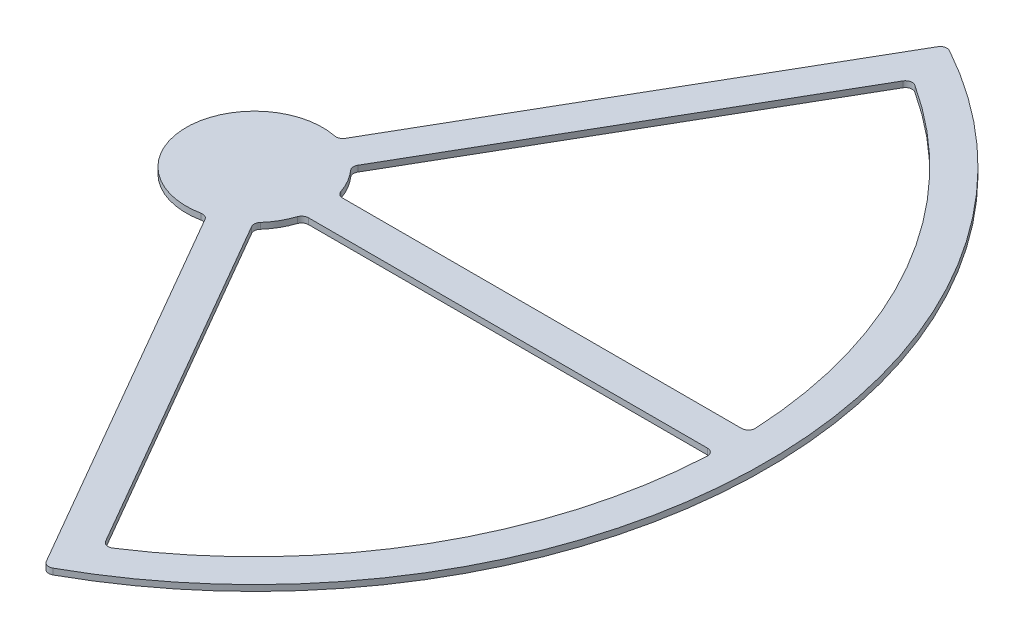
SolidWorks part; units mm, degrees
ref_plane "Front Plane" through (0, 0, 0) normal (0, 0, 1) x (1, 0, 0)
ref_plane "Top Plane" through (0, 0, 0) normal (0, 1, 0) x (1, 0, 0)
ref_plane "Right Plane" through (0, 0, 0) normal (1, 0, 0) x (0, 0, -1)
sketch "Sketch1" plane through (0, 0, 0) normal (0, 1, 0) x (1, 0, 0)
  line L0 (0, 0) -> (150, 0) construction
  line L1 (0, 0) -> (75, 129.9038) construction
  line L2 (0, 0) -> (75, -129.9038) construction
  line L3 (20.8567, 5) -> (137.8223, 5)
  line L4 (20.8567, -5) -> (137.8223, -5)
  line L5 (14.7585, 15.5624) -> (73.2413, 116.8577)
  line L6 (6.0982, 20.5624) -> (69.6547, 130.6454)
  line L7 (14.7585, -15.5624) -> (73.2413, -116.8577)
  line L8 (6.0982, -20.5624) -> (69.6547, -130.6454)
  arc A0 (3.9692, 19.6022) -> (3.9692, -19.6022) centre (0, 0) ccw
  arc A1 (139.8198, 7.1014) -> (76.0599, 117.5368) centre (0, 0) ccw
  arc A2 (72.3514, -131.3974) -> (72.3514, 131.3974) centre (0, 0) ccw
  arc A3 (18.9606, 6.3636) -> (14.9914, 13.2385) centre (0, 0) ccw
  arc A4 (14.9914, -13.2385) -> (18.9606, -6.3636) centre (0, 0) ccw
  arc A5 (76.0599, -117.5368) -> (139.8198, -7.1014) centre (0, 0) ccw
  arc A6 (69.6547, -130.6454) -> (72.3514, -131.3974) centre (71.3867, -129.6454) ccw
  arc A7 (6.0982, -20.5624) -> (3.9692, -19.6022) centre (4.3661, -21.5624) ccw
  arc A8 (73.2413, -116.8577) -> (76.0599, -117.5368) centre (74.9734, -115.8577) ccw
  arc A9 (14.7585, -15.5624) -> (14.9914, -13.2385) centre (16.4905, -14.5624) cw
  arc A10 (69.6547, 130.6454) -> (72.3514, 131.3974) centre (71.3867, 129.6454) cw
  arc A11 (6.0982, 20.5624) -> (3.9692, 19.6022) centre (4.3661, 21.5624) cw
  arc A12 (73.2413, 116.8577) -> (76.0599, 117.5368) centre (74.9734, 115.8577) cw
  arc A13 (137.8223, -5) -> (139.8198, -7.1014) centre (137.8223, -7) cw
  arc A14 (20.8567, -5) -> (18.9606, -6.3636) centre (20.8567, -7) ccw
  arc A15 (137.8223, 5) -> (139.8198, 7.1014) centre (137.8223, 7) ccw
  arc A16 (14.7585, 15.5624) -> (14.9914, 13.2385) centre (16.4905, 14.5624) ccw
  arc A17 (20.8567, 5) -> (18.9606, 6.3636) centre (20.8567, 7) cw
  point P25 (14.0126, -14.2705)
  point P27 (0.001, 0)
  point P43 (19.3649, 5)
  dimension "D1" = 10
  dimension "D10" = 20
  dimension "D11" = 150
  dimension "D12" = 2
  dimension "D2" = 10
  dimension "D3" = 60
  dimension "D4" = 5
  dimension "D5" = 60
  dimension "D6" = 5
  dimension "D7" = 10
  dimension "D8" = 5
  dimension "D9" = 10
extrude "Boss-Extrude1" add sketch "Sketch1" along normal blind 1.75
equation "\"d1\"= 1cm"
equation "\"D2@Sketch1\"=\"d1\""
equation "\"D4@Sketch1\"=\"d1\"/2"
equation "\"a1\"=60"
equation "\"D3@Sketch1\"=\"a1\""
equation "\"D5@Sketch1\"=\"a1\""
equation "\"D6@Sketch1\"=\"d1\"/2"
equation "\"D7@Sketch1\"=\"d1\""
equation "\"D8@Sketch1\"=\"d1\"/2"
equation "\"D9@Sketch1\"=\"d1\""
equation "\"D1@Sketch1\"=\"d1\""
equation "\"r1\"= 2cm"
equation "\"r2\"= 15cm"
equation "\"D11@Sketch1\"=\"r2\""
equation "\"D10@Sketch1\"=\"r1\""
